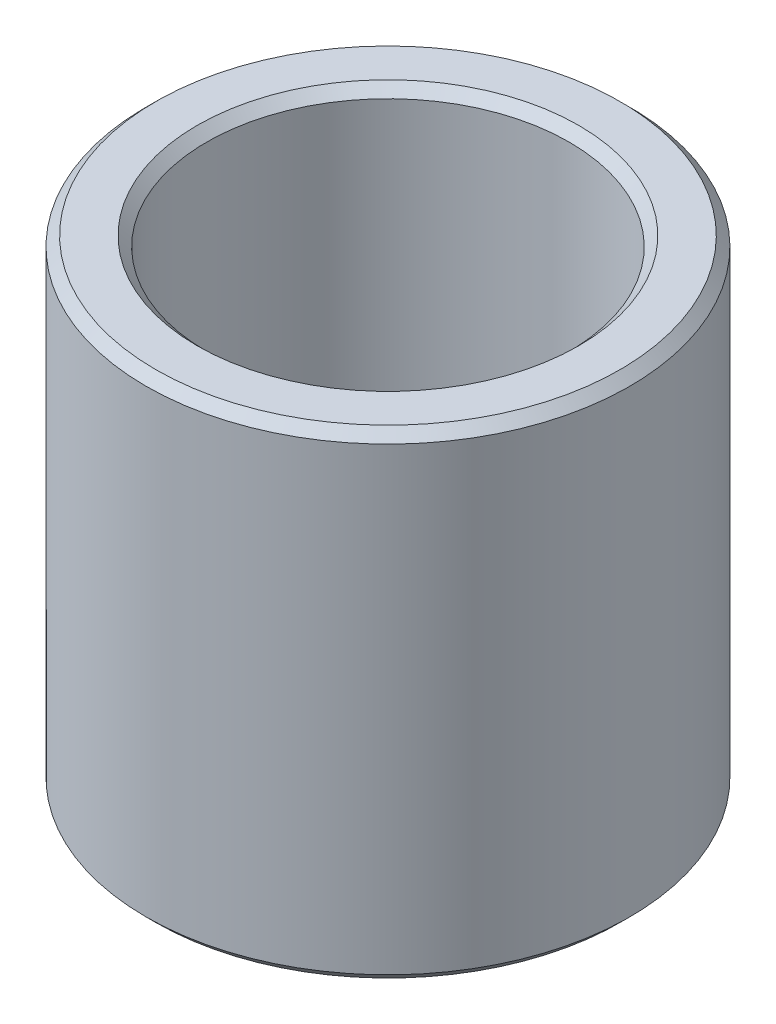
SolidWorks part; units mm, degrees
ref_plane "Front Plane" through (0, 0, 0) normal (0, 0, 1) x (1, 0, 0)
ref_plane "Top Plane" through (0, 0, 0) normal (0, 1, 0) x (1, 0, 0)
ref_plane "Right Plane" through (0, 0, 0) normal (1, 0, 0) x (0, 0, -1)
sketch "Sketch1" plane through (0, 0, 0) normal (0, 1, 0) x (1, 0, 0)
  circle A0 centre (0, 0) radius 4.7879
  circle A1 centre (0, 0) radius 6.3881
  dimension "D1" = 9.5758
  dimension "D2" = 12.7762
extrude "Boss-Extrude1" add sketch "Sketch1" along normal blind 12.6492
chamfer "Chamfer1" distance 0.254 angle 45 4 edges at (0, 12.6492, 6.3881) (0, 12.6492, 4.7879) (0, 0, 6.3881) (0, 0, 4.7879)
